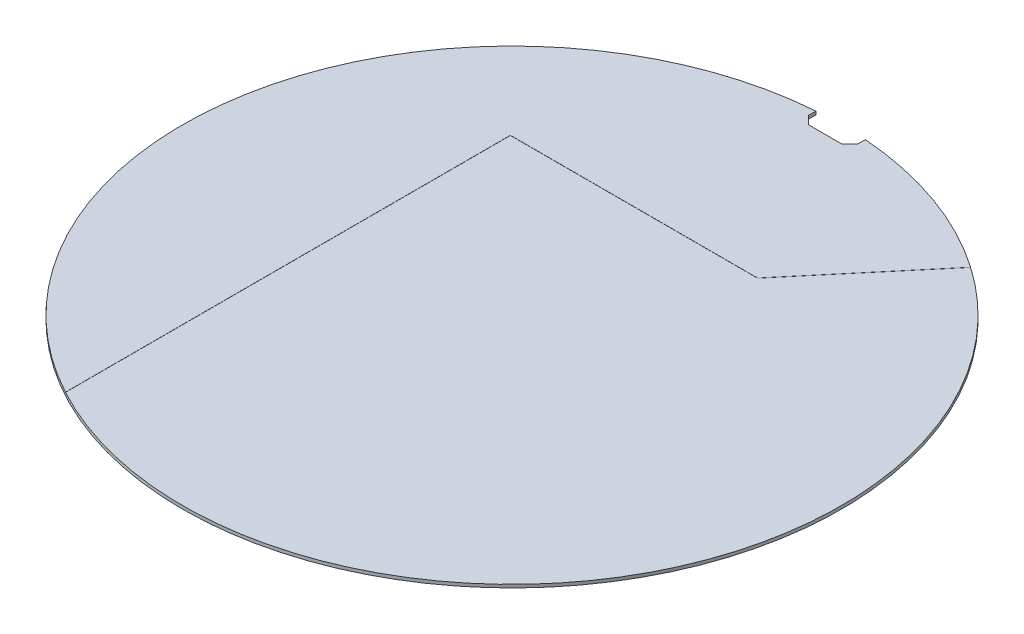
SolidWorks part; units mm, degrees
ref_plane "Front Plane" through (0, 0, 0) normal (0, 0, 1) x (1, 0, 0)
ref_plane "Top Plane" through (0, 0, 0) normal (0, 1, 0) x (1, 0, 0)
ref_plane "Right Plane" through (0, 0, 0) normal (1, 0, 0) x (0, 0, -1)
sketch "Sketch1" plane through (0, 0, 0) normal (0, 1, 0) x (1, 0, 0)
  circle A0 centre (0, 0) radius 20
  dimension "D1" = 40
extrude "Boss-Extrude1" add sketch "Sketch1" along normal blind 0.2
sketch "Sketch2" plane through (0, 0.2, 0) normal (0, 1, 0) x (1, 0, 0)
  line L6 (1.5, 19.5) -> (1.5, 19.9437)
  line L7 (1, 19) -> (1.5, 19.5)
  line L8 (-1, 19) -> (1, 19)
  line L9 (-1.5, 19.5) -> (-1, 19)
  line L10 (-1.5, 19.9437) -> (-1.5, 19.5)
  line L11 (1.5, 19.5) -> (1.5, 19.9437)
  line L12 (1, 19) -> (1.5, 19.5)
  line L13 (-1, 19) -> (1, 19)
  line L14 (-1.5, 19.5) -> (-1, 19)
  line L15 (-1.5, 19.9437) -> (-1.5, 19.5)
  arc A1 (1.5, 19.9437) -> (-1.5, 19.9437) centre (0, 0) ccw
  arc A2 (1.5, 19.9437) -> (-1.5, 19.9437) centre (0, 0) ccw
  dimension "D1" = 0
extrude "Cut-Extrude1" cut sketch "Sketch2" against normal through all
sketch "Sketch3" plane through (0, 0.2, 0) normal (0, 1, 0) x (1, 0, 0)
  line L0 (11.4007, 16.4324) -> (5.5, 9.4003)
  line L1 (5.5, 9.4003) -> (-9.5, 9.4003)
  line L2 (-9.5, 9.4003) -> (-9.5, -17.5997)
  arc A0 (-1.5, 19.9437) -> (1.5, 19.9437) centre (0, 0) ccw construction
  arc A1 (-1.5, 19.9437) -> (1.5, 19.9437) centre (0, 0) ccw
  arc M9 (-1.5, 19.9437) -> (1.5, 19.9437) centre (0, 0) ccw
  dimension "D1" = 27
  dimension "D2" = 10.5
  dimension "D3" = 130
  dimension "D4" = 15
extrude "Cut-Extrude2" cut sketch "Sketch3" against normal blind 0.01 contours L1 L2 L0 M9
